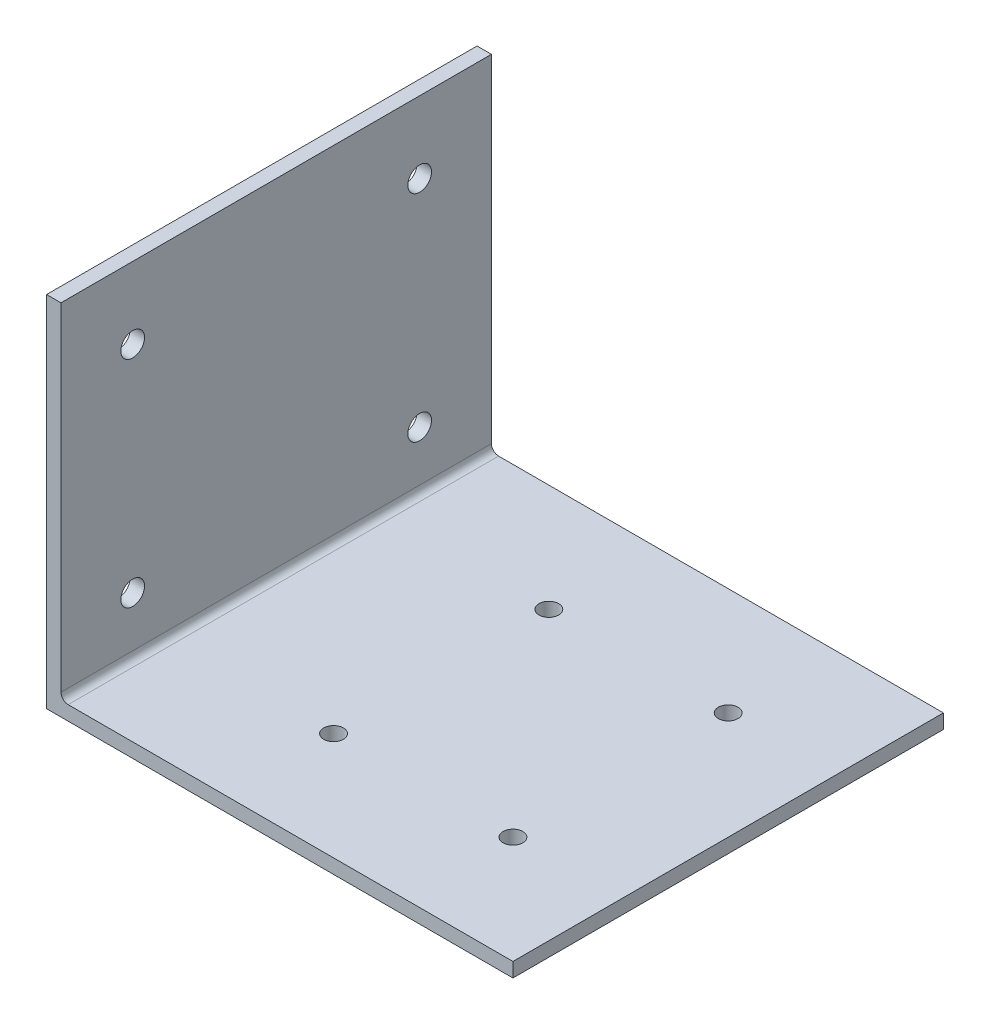
SolidWorks part; units mm, degrees
material "6061-T6 (SS)"
ref_plane "Front Plane" through (0, 0, 0) normal (0, 0, 1) x (1, 0, 0)
ref_plane "Top Plane" through (0, 0, 0) normal (0, 1, 0) x (1, 0, 0)
ref_plane "Right Plane" through (0, 0, 0) normal (1, 0, 0) x (0, 0, -1)
sketch "Sketch2" plane through (0, 0, 0) normal (0, 0, 1) x (1, 0, 0)
  line L0 (0, 0) -> (0, 100)
  line L1 (0, 100) -> (4, 100)
  line L2 (4, 100) -> (4, 4)
  line L3 (4, 4) -> (130, 4)
  line L4 (130, 4) -> (130, 0)
  line L5 (130, 0) -> (0, 0)
  dimension "D1" = 100
  dimension "D2" = 4
  dimension "D3" = 4
  dimension "D4" = 130
extrude "Boss-Extrude1" add sketch "Sketch2" along normal blind 120
sketch "Sketch4" plane through (4, 0, 0) normal (1, 0, 0) x (0, 0, -1)
  line L0 (0, 4) -> (0, 100) construction
  line L1 (-120, 100) -> (0, 100) construction
  circle A0 centre (-100, 80) radius 3.3
  circle A1 centre (-20, 80) radius 3.3
  circle A2 centre (-20, 20) radius 3.3
  circle A3 centre (-100, 20) radius 3.3
  point P8 (0, 0)
  point P9 (0, 0)
  point P10 (0, 0)
  dimension "D1" = 6.6
  dimension "D2" = 60
  dimension "D3" = 80
  dimension "D4" = 20
  dimension "D5" = 20
extrude "Cut-Extrude1" cut sketch "Sketch4" against normal through all
sketch "Sketch5" plane through (0, 4, 0) normal (0, 1, 0) x (1, 0, 0)
  line L0 (0, -120) -> (0, 0) construction
  line L1 (130, -120) -> (4, -120) construction
  circle A0 centre (100, -30) radius 2.75
  circle A1 centre (50, -30) radius 2.75
  circle A2 centre (50, -90) radius 2.75
  circle A3 centre (100, -90) radius 2.75
  point P8 (0, 0)
  point P9 (0, 0)
  point P10 (0, 0)
  dimension "D1" = 5.5
  dimension "D2" = 50
  dimension "D3" = 60
  dimension "D4" = 50
  dimension "D5" = 30
extrude "Cut-Extrude2" cut sketch "Sketch5" against normal through all
fillet "Fillet1" radius 2 1 edges at (4, 4, 60)
